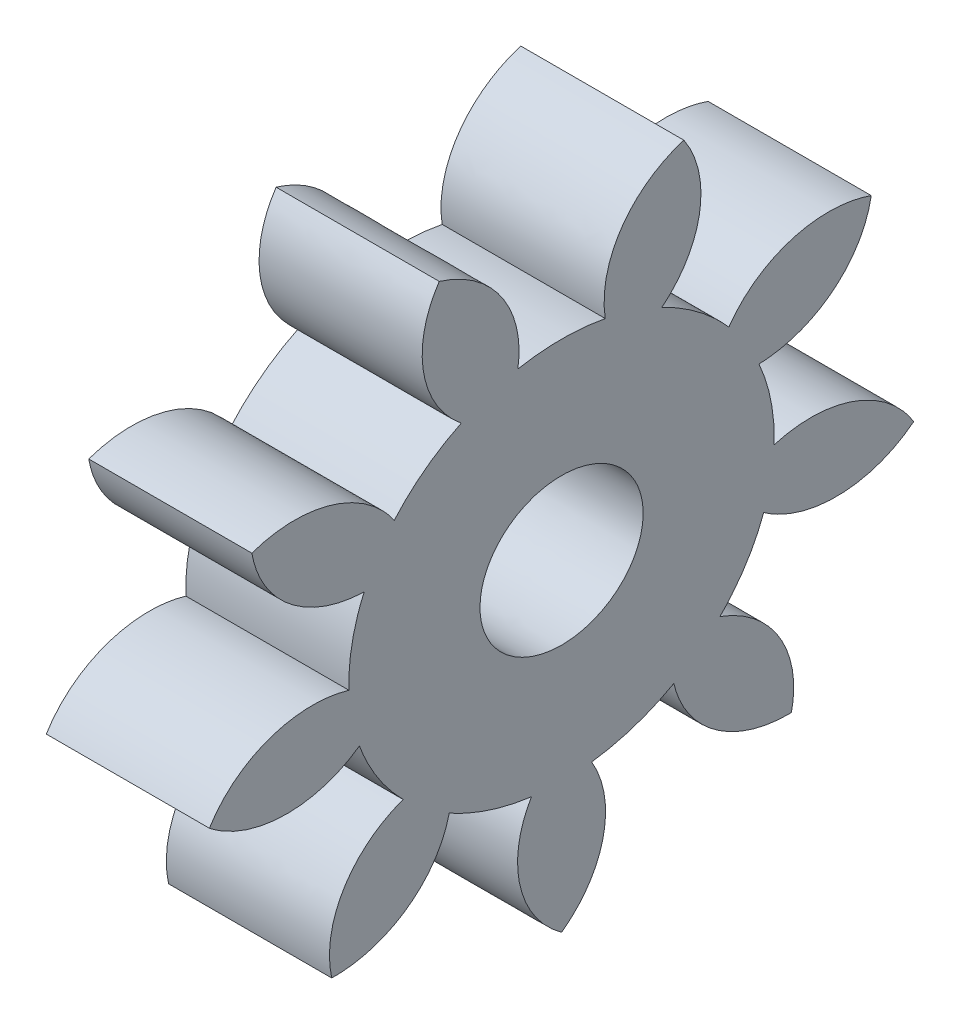
SolidWorks part; units mm, degrees
ref_plane "Plane1" through (0, 0, 0) normal (0, 0, 1) x (1, 0, 0)
ref_plane "Plane2" through (0, 0, 0) normal (0, 1, 0) x (1, 0, 0)
ref_plane "Plane3" through (0, 0, 0) normal (1, 0, 0) x (0, 0, -1)
sketch "HoldingSke" plane through (0, 0, 0) normal (0, 1, 0) x (1, 0, 0)
  line L0 (0, 0) -> (500.2823, -88.2133)
  line L1 (-15, 0) -> (100, 0) construction
  line L2 (0, 0) -> (-2.1039, 2.3779)
  line L3 (0, 0) -> (-11.863, 4.5341)
  line L4 (0, 0) -> (8.5048, 1.4996)
  line L5 (0, 0) -> (-47.5972, -17.7524)
  line L6 (0, 0) -> (-2.632, -1.7758)
  line L7 (-2.1039, 2.3779) -> (8.8308, 51.9871)
  line L8 (-76.2, 54.61) -> (-72.771, 54.61)
  line L9 (-71.009, 38.7566) -> (-53.1078, 45.2721)
  line L10 (-76.2, 71.12) -> (104.1128, 71.12)
  line L11 (0, 0) -> (-3.175, 0)
  line L12 (-76.2, 101.6) -> (-76.1492, 101.6)
  line L13 (24.9733, 27.94) -> (52.9518, 28.4284)
  line L14 (24.9733, 27.94) -> (25.0241, 27.9398)
  line L15 (24.9733, 27.94) -> (100.4021, 29.52)
  circle A0 centre (0, 0) radius 1.5875
  circle A1 centre (0, 0) radius 4.1402
  circle A2 centre (0, 0) radius 38.1
  circle A3 centre (0, 0) radius 1.5875
  dimension "MHD" = 8.2804
  dimension "Hub_dia" = 76.2
  dimension "Bore" = 3.175
  dimension "MBD" = 3.175
  dimension "Num_teeth" = 10
  dimension "Pitch_radius" = 180.3128
  dimension "Pitch" = 508
  dimension "Width" = 3.175
  dimension "Overall_len" = 50.8
  dimension "Show_teeth" = 10
  dimension "Thickness" = 3.175
  dimension "OAL" = 50.8001
  dimension "T_dim" = 3.429
  dimension "Ap" = 20
  dimension "H" = 19.05
  dimension "Backlash" = 0.0508
  dimension "Addendum_fac" = 1
  dimension "Dedendum_fac" = 1.2
  dimension "Clearance_fac" = 0.2
  dimension "Dedendum_add" = 0.0508
sketch "BasProSke" plane through (0, 0, 0) normal (0, 1, 0) x (1, 0, 0)
  line L0 (-10, 0) -> (60, 0) construction
  line L1 (0, 0) -> (0, 6.985)
  line L2 (0, 0) -> (3.175, 0)
  line L3 (3.175, 0) -> (3.175, 6.985)
  line L4 (3.175, 6.985) -> (0, 6.985)
  dimension "Diameter" = 13.97
  dimension "Thickness" = 3.175
revolve "Base-Revolve" add sketch "BasProSke" angle 360 about L0
sketch "TooCutSke" plane through (0, 0, 0) normal (1, 0, 0) x (0, 0, -1)
  line L1 (0, 0) -> (0, 107) construction
  line L2 (0, 0) -> (-1.1786, 5.5922) construction
  line L3 (0, 0) -> (-3.8703, 10.6336) construction
  line L4 (-1.1786, 5.5922) -> (-1.9352, 5.3168) construction
  arc A0 (0.8509, 4.0518) -> (-0.8509, 4.0518) centre (0, 0) ccw
  arc A1 (2.4581, 6.5653) -> (-2.4581, 6.5653) centre (0, 0) ccw
  circle A2 centre (0, 0) radius 5.715 construction
  circle A3 centre (0, 0) radius 5.3703 construction
  arc A4 (-0.8509, 4.0518) -> (-2.4581, 6.5653) centre (-3.1139, 4.3754) ccw
  arc A5 (2.4581, 6.5653) -> (0.8509, 4.0518) centre (3.1139, 4.3754) ccw
  dimension "Root_dia" = 8.2804
  dimension "Overcut_dia" = 14.0208
  dimension "Pitch_dia" = 11.43
  dimension "Base_dia" = 10.7407
  dimension "Flank_rad" = 2.286
  dimension "Half_ang" = 20
  dimension "Half_CT" = 0.8051
extrude "ToothCut" cut sketch "TooCutSke" along normal through all
fillet "Breaks" [suppressed] radius 0.0254
fillet "RootFillets" [suppressed] radius 0.3048
pattern_circular "TeethCuts" count 10 every 40 about axis through (-10, 0, 0) along (1, 0, 0) of "ToothCut"
sketch "HubNeaOneSke" plane through (0, 0, 0) normal (-1, 0, 0) x (0, 0, 1)
  circle A0 centre (0, 0) radius 4.1402
  dimension "Diameter" = 8.2804
extrude "HubNearOne" [suppressed] add sketch "HubNeaOneSke" along normal blind 47.6251
sketch "HubNeaBotSke" plane through (0, 0, 0) normal (-1, 0, 0) x (0, 0, 1)
  circle A0 centre (0, 0) radius 4.1402
  dimension "Diameter" = 8.2804
extrude "HubNearBoth" [suppressed] add sketch "HubNeaBotSke" along normal blind 23.8125
ref_plane "FarPln" through (3.175, 0, 0) normal (1, 0, 0) x (0, 0, -1)
sketch "HubFarSke" plane through (3.175, 0, 0) normal (1, 0, 0) x (0, 0, -1)
  circle A0 centre (0, 0) radius 4.1402
  dimension "Diameter" = 8.2804
extrude "HubFar" [suppressed] add sketch "HubFarSke" along normal blind 23.8125
sketch "BorSke" plane through (0, 0, 0) normal (1, 0, 0) x (0, 0, -1)
  circle A0 centre (0, 0) radius 1.5875
  dimension "Diameter" = 3.175
extrude "Bore" cut sketch "BorSke" along normal mid plane 101.6001
sketch "KeySke" plane through (0, 0, 0) normal (1, 0, 0) x (0, 0, -1)
  line L0 (-0.127, 0) -> (-0.127, 1.8415)
  line L1 (-0.127, 1.8415) -> (0.127, 1.8415)
  line L2 (0.127, 1.8415) -> (0.127, 0)
  line L3 (0, 0) -> (0, 34) construction
  line L4 (-0.127, 0) -> (0.127, 0)
  dimension "Offset" = 1.8415
  dimension "Width" = 0.254
extrude "Keyway" [suppressed] cut sketch "KeySke" along normal mid plane 101.6001
pattern_circular "Keyway2" [suppressed] count 2 every 90 about axis through (-10, 0, 0) along (1, 0, 0)
scale "Scale1" scale about centroid uniform scaling no x scale factor 1.11 y scale factor 1 z scale factor 1.11
equation "' \"Pitch@HoldingSke\" = 4"
equation "' \"Num_teeth@HoldingSke\" = 12"
equation "' \"Ap@HoldingSke\" =  20"
equation "' \"Width@HoldingSke\" = 0.5"
equation "' \"Hub_dia@HoldingSke\"= 1"
equation "' \"Overall_len@HoldingSke\" = 1.0"
equation "' \"Bore@HoldingSke\" = 0.75"
equation "' \"T_dim@HoldingSke\" = 0.85"
equation "' \"Width@KeySke\" = 0.25"
equation "' \"Show_teeth@HoldingSke\" = 13"
equation "' \"Backlash@HoldingSke\" = 0.009"
equation "' \"Addendum_fac@HoldingSke\" = 1.0"
equation "' \"Dedendum_fac@HoldingSke\" = 1.25"
equation "' \"Dedendum_add@HoldingSke\" = 0.00005"
equation "' \"Clearance_fac@HoldingSke\" = 0.25"
equation "' \"Pitch@HoldingSke\" = 0.5"
equation "' \"Num_teeth@HoldingSke\" = 23"
equation "' \"Show_teeth@HoldingSke\" = 23"
equation "' \"Backlash@HoldingSke\" = 0.0375"
equation "\"Overcut_dia@TooCutSke\"=(9 + 2 * \"Addendum_fac@HoldingSke\") / \"Pitch@HoldingSke\" + 0.002"
equation "\"Pitch_dia@TooCutSke\"=9/ \"Pitch@HoldingSke\""
equation "\"Base_dia@TooCutSke\"=9 / \"Pitch@HoldingSke\" * cos((\"Ap@HoldingSke\"  * 3.14159265 / 180))"
equation "\"Root_dia@TooCutSke\"=(9 + 2) / \"Pitch@HoldingSke\" - 2 * (\"Addendum_fac@HoldingSke\" + \"Dedendum_fac@HoldingSke\") / \"Pitch@HoldingSke\" - \"Dedendum_add@HoldingSke\" * 2"
equation "\"Half_ang@TooCutSke\"=180 / 9"
equation "\"Half_CT@TooCutSke\"=9 / \"Pitch@HoldingSke\" * sin((3.14159265 / 2 / \"Num_teeth@HoldingSke\")) / 2 - 7 * \"Backlash@HoldingSke\" / 4"
equation "\"Flank_rad@TooCutSke\"=9/ \"Pitch@HoldingSke\" / 5"
equation "\"Radius@RootFillets\" = \"Clearance_fac@HoldingSke\" / \"Pitch@HoldingSke\" + \"Dedendum_add@HoldingSke\""
equation "\"Break_rad@Breaks\" = 0.02 / \"Pitch@HoldingSke\""
equation "\"Thickness@HoldingSke\" = \"Width@HoldingSke\""
equation "\"OAL@HoldingSke\" = \"Thickness@HoldingSke\""
equation "\"MHD@HoldingSke\" = (\"Num_teeth@HoldingSke\" + 2) / \"Pitch@HoldingSke\" - 2 * (\"Addendum_fac@HoldingSke\" + \"Dedendum_fac@HoldingSke\")  / \"Pitch@HoldingSke\" - \"Dedendum_add@HoldingSke\" * 2"
equation "\"MBD@HoldingSke\" = (\"Num_teeth@HoldingSke\" + 2) / \"Pitch@HoldingSke\" - 2 * (\"Addendum_fac@HoldingSke\" + \"Dedendum_fac@HoldingSke\")  / \"Pitch@HoldingSke\" - \"Dedendum_add@HoldingSke\" * 2 - 0.002"
equation "\"MHD@HoldingSke\" = ((sgn( \"MHD@HoldingSke\" - \"Hub_dia@HoldingSke\" )-1)*( \"MHD@HoldingSke\" - \"Hub_dia@HoldingSke\" ))/-2+ \"Hub_dia@HoldingSke\""
equation "\"MBD@HoldingSke\" = ((sgn( \"MBD@HoldingSke\" - \"Bore@HoldingSke\" )-1)*( \"MBD@HoldingSke\" - \"Bore@HoldingSke\" ))/-2+ \"Bore@HoldingSke\""
equation "\"OAL@HoldingSke\" = ((sgn( \"OAL@HoldingSke\" - \"Overall_len@HoldingSke\" )+1)*( \"OAL@HoldingSke\" - \"Overall_len@HoldingSke\" ))/2 + \"Overall_len@HoldingSke\" + 0.000002"
equation "\"Num_teeth@TeethCuts\"=int( 9 ) + 1"
equation "\"Num_teeth@TeethCuts\" = ((sgn( \"Num_teeth@TeethCuts\" - \"Num_teeth@HoldingSke\" )-1)*( \"Num_teeth@TeethCuts\" - \"Num_teeth@HoldingSke\" ))/-2+ \"Num_teeth@HoldingSke\""
equation "\"Num_teeth@TeethCuts\" = ((sgn( \"Num_teeth@TeethCuts\" - 2.0)+1)*( \"Num_teeth@TeethCuts\" - 2.0))/2 +2.0"
equation "\"Angle@TeethCuts\"=360.0 / 9"
equation "\"Diameter@BasProSke\"=(9 + 2 * \"Addendum_fac@HoldingSke\") / \"Pitch@HoldingSke\""
equation "\"Thickness@BasProSke\"=.125"
equation "' \"Fillet_rad@BasProSke\" =  \"Thickness@HoldingSke\" * 0.05"
equation "\"MHD@HoldingSke\" = ((sgn( \"MHD@HoldingSke\" - \"Root_dia@TooCutSke\" )-1)*( \"MHD@HoldingSke\" - \"Root_dia@TooCutSke\" ))/-2+ \"Root_dia@TooCutSke\""
equation "\"Diameter@HubNeaOneSke\" = \"MHD@HoldingSke\""
equation "\"Length@HubNearOne\" = \"OAL@HoldingSke\" - \"Thickness@BasProSke\""
equation "\"Diameter@HubNeaBotSke\" = \"MHD@HoldingSke\""
equation "\"Length@HubNearBoth\" = ( \"OAL@HoldingSke\" - \"Thickness@BasProSke\" ) / 2.0"
equation "\"Thickness@FarPln\" = \"Thickness@BasProSke\""
equation "\"Diameter@HubFarSke\" = \"MHD@HoldingSke\""
equation "\"Length@HubFar\" = ( \"OAL@HoldingSke\" - \"Thickness@BasProSke\" ) / 2.0"
equation "\"Diameter@BorSke\" = \"MBD@HoldingSke\""
equation "\"D1@Bore\" = \"OAL@HoldingSke\" * 2.0"
equation "\"D1@Keyway\" = \"OAL@HoldingSke\" * 2.0"
equation "\"Offset@KeySke\" = \"T_dim@HoldingSke\" - \"MBD@HoldingSke\" / 2.0"
